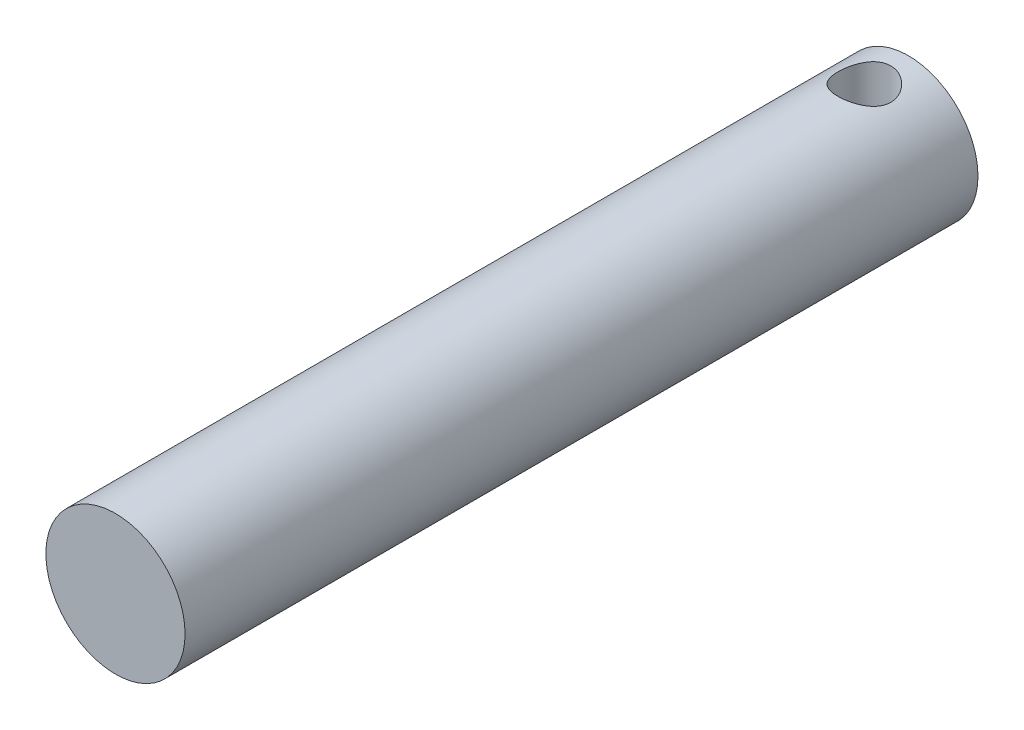
SolidWorks part; units mm, degrees
ref_plane "Front Plane" through (0, 0, 0) normal (0, 0, 1) x (1, 0, 0)
ref_plane "Top Plane" through (0, 0, 0) normal (0, 1, 0) x (1, 0, 0)
ref_plane "Right Plane" through (0, 0, 0) normal (1, 0, 0) x (0, 0, -1)
sketch "Sketch1" plane through (0, 0, 0) normal (0, 0, 1) x (1, 0, 0)
  circle A0 centre (0, 0) radius 3.95
  dimension "D1" = 7.9
extrude "Boss-Extrude1" add sketch "Sketch1" along normal blind 45
sketch "Sketch2" plane through (0, 0, 0) normal (0, 1, 0) x (1, 0, 0)
  circle A0 centre (0, -2.5) radius 1.5
  dimension "D1" = 3
  dimension "D2" = 2.5
extrude "Cut-Extrude1" cut sketch "Sketch2" against normal through all both and the other way through all
